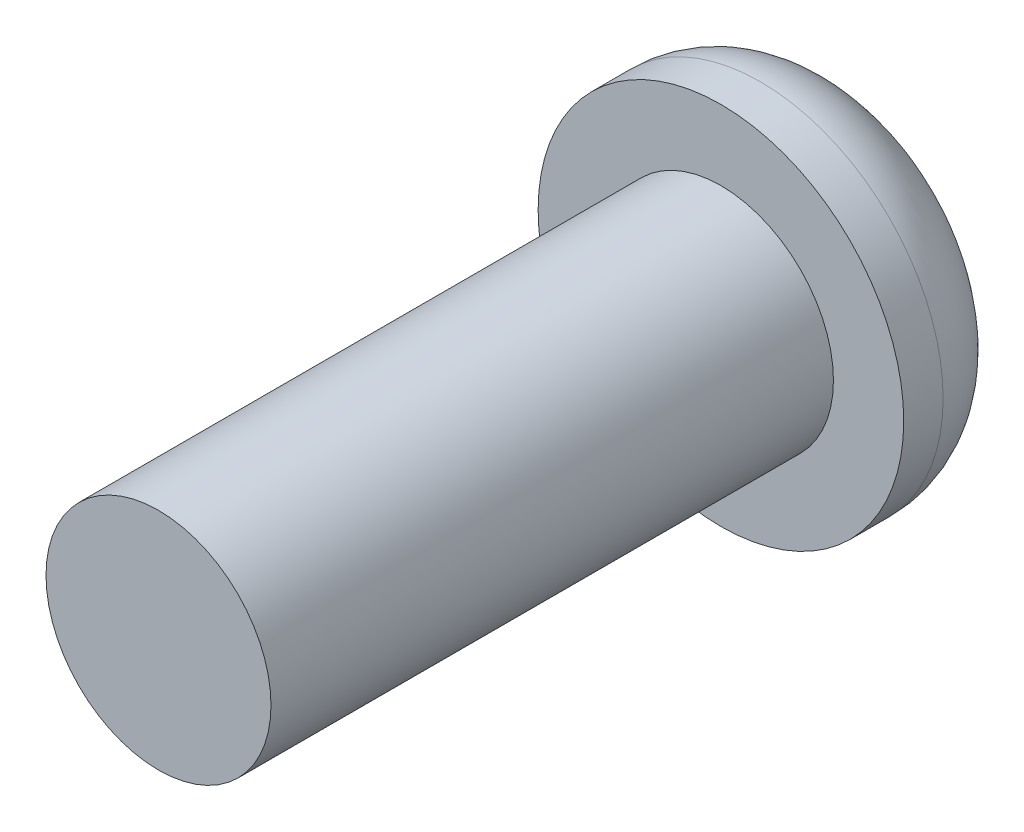
SolidWorks part; units mm, degrees
ref_plane "前视基准面" through (0, 0, 0) normal (0, 0, 1) x (1, 0, 0)
ref_plane "上视基准面" through (0, 0, 0) normal (0, 1, 0) x (1, 0, 0)
ref_plane "右视基准面" through (0, 0, 0) normal (1, 0, 0) x (0, 0, -1)
sketch "草图1" plane through (0, 0, 0) normal (0, 0, 1) x (1, 0, 0)
  circle A0 centre (0, 0) radius 2
extrude "凸台-拉伸1" add sketch "草图1" along normal blind 10
sketch "草图2" plane through (0, 0, 0) normal (0, 0, -1) x (-1, 0, 0)
  circle A0 centre (0, 0) radius 3.25
extrude "凸台-拉伸2" add sketch "草图2" along normal blind 2.2
fillet "圆角1" radius 1.5 1 edges at (-3.25, 0, -2.2)
thread "螺纹线1" pitch 0.9071 start angle 0, offset 0, length 0, pitch 0.9071, diameter 4
ref_plane "基准面1" through (2, 0, 0) normal (0, -1, 0) x (1, 0, 0)
sketch "螺纹线轮廓1" plane through (2, 0, 0) normal (0, -1, 0) x (1, 0, 0)
  line L0 (0, 0) -> (0, 0.9071) construction
  line L11 (0, 0) -> (0, 0.7937)
  line L12 (0, 0.7937) -> (-0.491, 0.5103)
  line L13 (-0.491, 0.5103) -> (-0.491, 0.2835)
  line L15 (-0.491, 0.2835) -> (0, 0)
  line L17 (-0.491, 0.3969) -> (0, 0.3969) construction
  point P2 (0, 0)
  dimension "Pitch" = 0.9071
  dimension "Profile_Angle" = 60
  dimension "Profile_Land" = 0.2268
  dimension "Profile_Height" = 0.491
